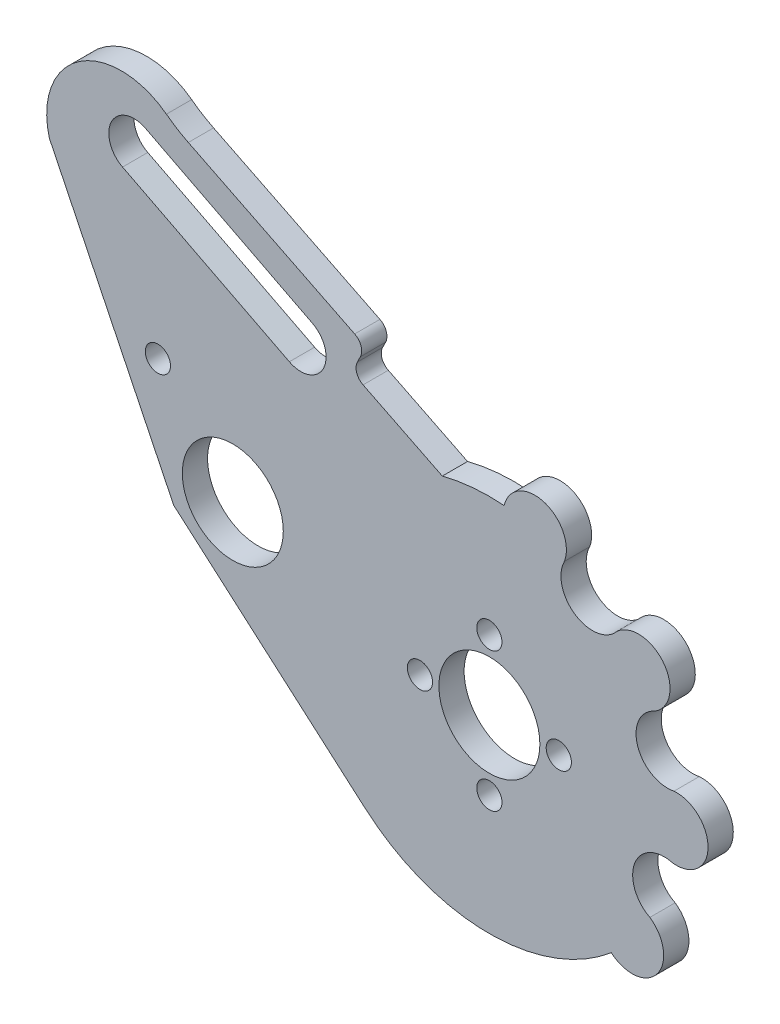
SolidWorks part; units mm, degrees
ref_plane "Plan de face" through (0, 0, 0) normal (0, 0, 1) x (1, 0, 0)
ref_plane "Plan de dessus" through (0, 0, 0) normal (0, 1, 0) x (1, 0, 0)
ref_plane "Plan de droite" through (0, 0, 0) normal (1, 0, 0) x (0, 0, -1)
sketch "Esquisse1" plane through (0, 0, 0) normal (0, 0, 1) x (1, 0, 0)
  line L0 (-10.9021, 18.0926) -> (-3.7284, 14.5292)
  line L1 (-10.9021, 18.0926) -> (-9.7741, 20.3635)
  line L2 (-9.7741, 20.3635) -> (-25.0053, 27.9292)
  line L3 (-34.8561, 22.147) -> (-25.0053, 1.8844)
  line L4 (-25.0053, 1.8844) -> (-2.2341, -17.9446)
  line L5 (-28.148, 24.8441) -> (-14.936, 18.0926) construction
  line L6 (-27.2379, 26.625) -> (-14.0259, 19.8736)
  line L7 (-29.0581, 23.0631) -> (-15.846, 16.3117)
  circle A1 centre (3.6018, 14.3836) radius 2.5
  circle A2 centre (0, 0) radius 15 construction
  circle A3 centre (8.1697, 12.374) radius 2.5
  circle A4 centre (0, 0) radius 15 construction
  circle A5 centre (11.8121, 8.9629) radius 2.5
  circle A6 centre (0, 0) radius 15
  circle A7 centre (14.1167, 4.5365) radius 2.5
  circle A8 centre (0, 0) radius 15
  circle A9 centre (14.8222, -0.4037) radius 2.5
  circle A10 centre (0, 0) radius 15
  circle A11 centre (13.8488, -5.2982) radius 2.5
  circle A12 centre (0, 0) radius 15
  circle A13 centre (11.3068, -9.5925) radius 2.5
  circle A14 centre (0, 0) radius 15
  arc A15 (-25.0053, 27.9292) -> (-34.8561, 22.147) centre (-29.1494, 23.7071) ccw
  circle A16 centre (0, 0) radius 4
  arc A17 (-27.2379, 26.625) -> (-29.0581, 23.0631) centre (-28.148, 24.8441) ccw
  circle A18 centre (0, 5.5) radius 1
  circle A19 centre (5.5, 0) radius 1
  circle A20 centre (0, -5.5) radius 1
  circle A21 centre (-5.5, 0) radius 1
  arc A23 (-15.846, 16.3117) -> (-14.0259, 19.8736) centre (-14.936, 18.0926) ccw
  circle A24 centre (-20.3252, 4.4391) radius 4
  circle A25 centre (-26.2564, 11.3193) radius 1
  point P27 (0, 0)
  point P34 (-21.542, 21.4683)
  point P38 (0, 0)
  point P49 (0, 0)
  dimension "D1" = 2
  dimension "D2" = 2
  dimension "D3" = 5
  dimension "D5" = 4
  dimension "D6" = 8
  dimension "D7" = 8
  dimension "D9" = 5
  dimension "D8" = 2
  dimension "D10" = 3
  dimension "D4" = 7
extrude "Boss.-Extru.1" add sketch "Esquisse1" along normal blind 2 contours A13 A11 A9 A7 A5 A3 A1 A2 A21 A20 A19 A18 A16 | L2 A15 L3 L4 A2 L0 L1 A25 A24 A23 L7 A17 L6 | A3 A1 A2 | A2 A1 | A7 A5 A4 A3 | A4 A5 | A11 A9 A8 A7 | A8 A9 | A12 A13 A11 | A12 A13
fillet "Congé1" radius 1 2 edges at (-10.9021, 18.0926, 1) (-9.7741, 20.3635, 1)
fillet "Congé2" radius 11 1 edges at (-25.0053, 27.9292, 1)
